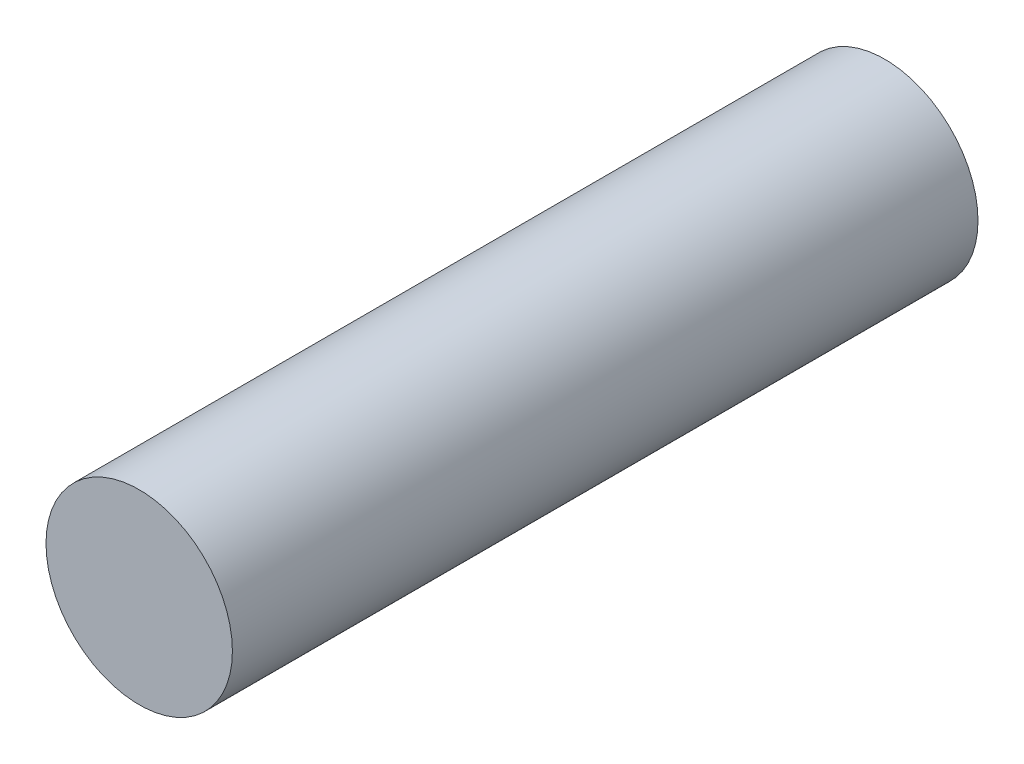
SolidWorks part; units mm, degrees
ref_plane "Front Plane" through (0, 0, 0) normal (0, 0, 1) x (1, 0, 0)
ref_plane "Top Plane" through (0, 0, 0) normal (0, 1, 0) x (1, 0, 0)
ref_plane "Right Plane" through (0, 0, 0) normal (1, 0, 0) x (0, 0, -1)
sketch "Sketch1" plane through (0, 0, 0) normal (0, 0, 1) x (1, 0, 0)
  circle A0 centre (0, 0) radius 6.35
  dimension "D1" = 12.7
extrude "Boss-Extrude1" add sketch "Sketch1" along normal mid plane 50.8
